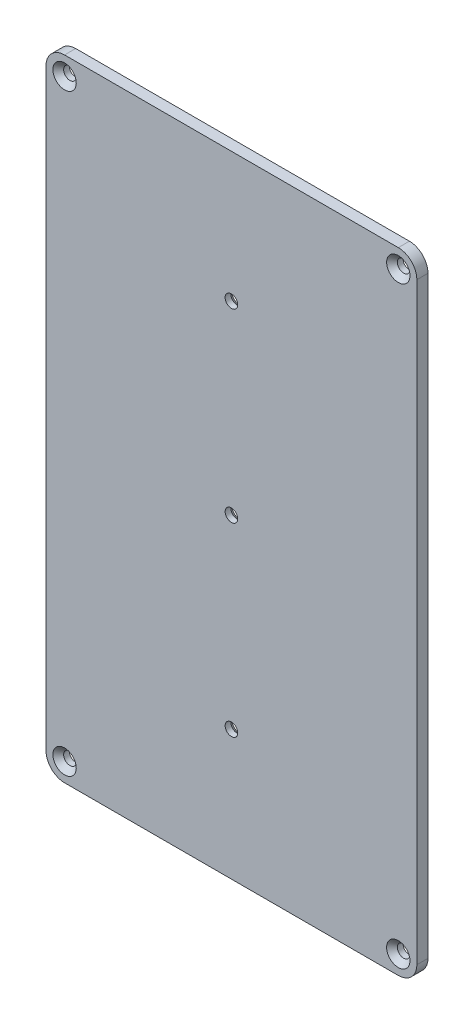
SolidWorks part; units mm, degrees
ref_plane "Front Plane" through (0, 0, 0) normal (0, 0, 1) x (1, 0, 0)
ref_plane "Top Plane" through (0, 0, 0) normal (0, 1, 0) x (1, 0, 0)
ref_plane "Right Plane" through (0, 0, 0) normal (1, 0, 0) x (0, 0, -1)
sketch "Sketch1" plane through (0, 0, 0) normal (0, 0, 1) x (1, 0, 0)
  line L1 (0, 0) -> (100, 0)
  line L2 (0, 0) -> (0, 170)
  line L3 (0, 170) -> (100, 170)
  line L4 (100, 0) -> (100, 170)
  dimension "D1" = 100
  dimension "D2" = 170
extrude "Boss-Extrude1" add sketch "Sketch1" along normal blind 3
hole_wizard "CSK for M3 Flat Head Machine Screw1" positions "Sketch4" profile "Sketch5" countersink size "M3" standard "ANSI Metric"
sketch "Sketch4" plane through (0, 0, 3) normal (0, 0, 1) x (1, 0, 0)
  line L0 (5, 165) -> (5, 85) construction
  line L1 (5, 85) -> (5, 5) construction
  line L2 (5, 5) -> (50, 5) construction
  line L3 (50, 5) -> (95, 5) construction
  line L4 (95, 5) -> (95, 85) construction
  line L5 (95, 85) -> (95, 165) construction
  line L6 (95, 165) -> (50, 165) construction
  line L7 (50, 165) -> (5, 165) construction
  line L10 (0, 170) -> (0, 0) construction
  line L11 (100, 170) -> (0, 170) construction
  line L12 (100, 0) -> (100, 170) construction
  line L13 (0, 0) -> (100, 0) construction
  point P0 (5, 165)
  point P4 (95, 165)
  point P8 (95, 5)
  point P12 (5, 5)
  dimension "D1" = 5
  dimension "D2" = 5
  dimension "D3" = 5
  dimension "D4" = 5
sketch "Sketch5" plane through (5, 165, 3) normal (1, 0, 0) x (0, -1, 0)
  line L0 (0, 0) -> (0, 8.5215)
  line L1 (0, 8.5215) -> (1.7, 7.5)
  line L2 (1.7, 7.5) -> (1.7, 1.45)
  line L3 (1.7, 1.45) -> (3.15, 0)
  line L5 (3.15, 0) -> (0, 0)
  line L6 (-1.7, 1.45) -> (-3.15, 0) construction
  line L10 (0, 8.5215) -> (-1.7, 7.5) construction
  line L11 (0, -6.35) -> (0, 107.95) construction
  dimension "Hole Dia." = 3.4
  dimension "Hole Depth" = 7.5
  dimension "Near C'Sink Dia." = 6.3
  dimension "Near C'Sink Angle" = 90
  dimension "Drill Angle" = 118
fillet "Fillet1" radius 5 4 edges at (100, 170, 1.5) (100, 0, 1.5) (0, 0, 1.5) (0, 170, 1.5)
hole_wizard "CSK for M3 Flat Head Machine Screw2" positions "Sketch6" profile "Sketch7" countersink size "M3" standard "ANSI Metric"
sketch "Sketch6" plane through (0, 0, 0) normal (0, 0, -1) x (-1, 0, 0)
  line L0 (-50, 35) -> (-50, 135) construction
  line L3 (-95, 170) -> (-5, 170) construction
  line L4 (-100, 5) -> (-100, 165) construction
  point P0 (-50, 135)
  point P2 (-50, 85)
  point P4 (-50, 35)
  point P12 (-50, 170)
  point P15 (-100, 85)
  point P16 (-50, 85)
  dimension "D1" = 100
sketch "Sketch7" plane through (50, 135, 0) normal (1, 0, 0) x (0, 1, 0)
  line L0 (0, 0) -> (0, 8.5215)
  line L1 (0, 8.5215) -> (1.7, 7.5)
  line L2 (1.7, 7.5) -> (1.7, 1.45)
  line L3 (1.7, 1.45) -> (3.15, 0)
  line L5 (3.15, 0) -> (0, 0)
  line L6 (-1.7, 1.45) -> (-3.15, 0) construction
  line L10 (0, 8.5215) -> (-1.7, 7.5) construction
  line L11 (0, -6.35) -> (0, 107.95) construction
  dimension "Hole Dia." = 3.4
  dimension "Hole Depth" = 7.5
  dimension "Near C'Sink Dia." = 6.3
  dimension "Near C'Sink Angle" = 90
  dimension "Drill Angle" = 118
